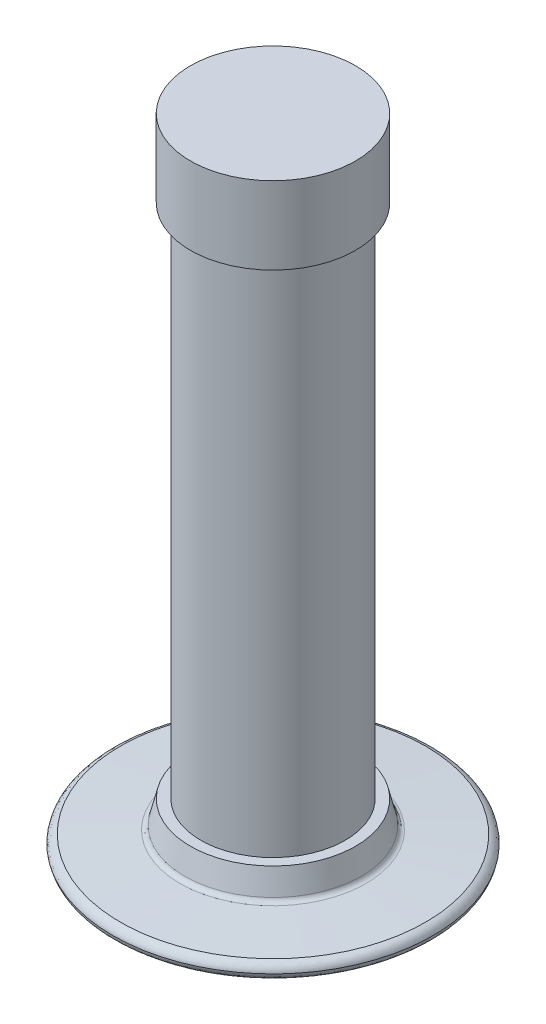
SolidWorks part; units mm, degrees
ref_plane "Front Plane" through (0, 0, 0) normal (0, 0, 1) x (1, 0, 0)
ref_plane "Top Plane" through (0, 0, 0) normal (0, 1, 0) x (1, 0, 0)
ref_plane "Right Plane" through (0, 0, 0) normal (1, 0, 0) x (0, 0, -1)
sketch "Sketch1" plane through (0, 0, 0) normal (0, 0, 1) x (1, 0, 0)
  line L0 (0, 0) -> (0, 130)
  line L1 (0, 130) -> (16, 130)
  line L2 (16, 130) -> (16, 115)
  line L3 (16, 115) -> (14, 115)
  line L4 (14, 15) -> (14, 115)
  line L5 (0, 0) -> (16, 0)
  line L6 (16, 0) -> (16, 15) construction
  line L7 (16, 7.5) -> (31, 7.5) construction
  line L8 (16, 0) -> (17.1117, 4.4876)
  line L9 (18.0203, 5.2452) -> (29.5645, 5.9633)
  line L10 (18.0203, 9.7548) -> (29.5645, 9.0367)
  line L11 (16, 15) -> (17.1117, 10.5124)
  line L12 (16, 15) -> (14, 15)
  arc A0 (18.0203, 5.2452) -> (17.1117, 4.4876) centre (18.0824, 4.2471) ccw
  arc A1 (18.0203, 9.7548) -> (17.1117, 10.5124) centre (18.0824, 10.7529) cw
  spline S0 degree 2 poles (29.5645, 5.9633) (30.8531, 6.3859) (31, 7.5) knots 0 0 0 1 1 1
  spline S1 degree 2 poles (29.5645, 9.0367) (30.8531, 8.6141) (31, 7.5) knots 0 0 0 1 1 1
  point P7 (29.5645, 5.9633)
  point P14 (17.1117, 4.4876)
  dimension "D8" = 1
  dimension "D1" = 130
  dimension "D2" = 16
  dimension "D3" = 15
  dimension "D4" = 2
  dimension "D5" = 15
  dimension "D6" = 16
  dimension "D7" = 15
  dimension "D9" = 2
revolve "Revolve1" add sketch "Sketch1" angle 360 about L0
